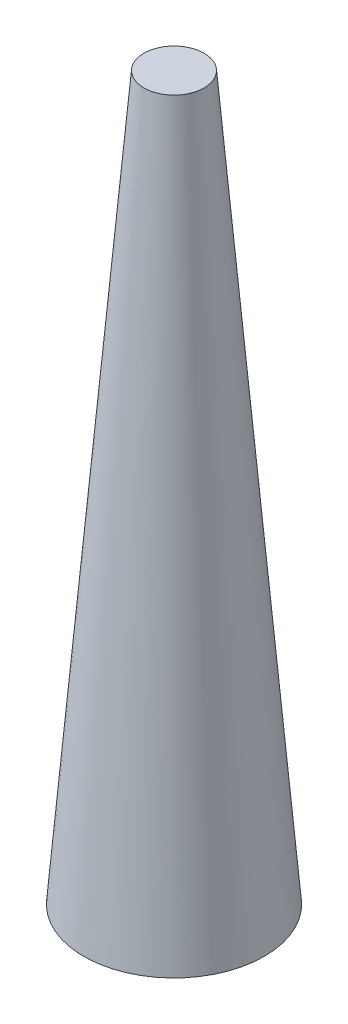
SolidWorks part; units mm, degrees
ref_plane "Front Plane" through (0, 0, 0) normal (0, 0, 1) x (1, 0, 0)
ref_plane "Top Plane" through (0, 0, 0) normal (0, 1, 0) x (1, 0, 0)
ref_plane "Right Plane" through (0, 0, 0) normal (1, 0, 0) x (0, 0, -1)
sketch "Sketch1" plane through (0, 0, 0) normal (0, 0, 1) x (1, 0, 0)
  line L0 (0, 0) -> (-19.05, 0)
  line L1 (-19.05, 0) -> (-6.35, 152.4)
  line L2 (-6.35, 152.4) -> (0, 152.4)
  line L3 (0, 152.4) -> (0, 0)
  dimension "D1" = 19.05
  dimension "D2" = 6.35
  dimension "D3" = 152.4
revolve "Revolve1" add sketch "Sketch1" angle 360 about L3
